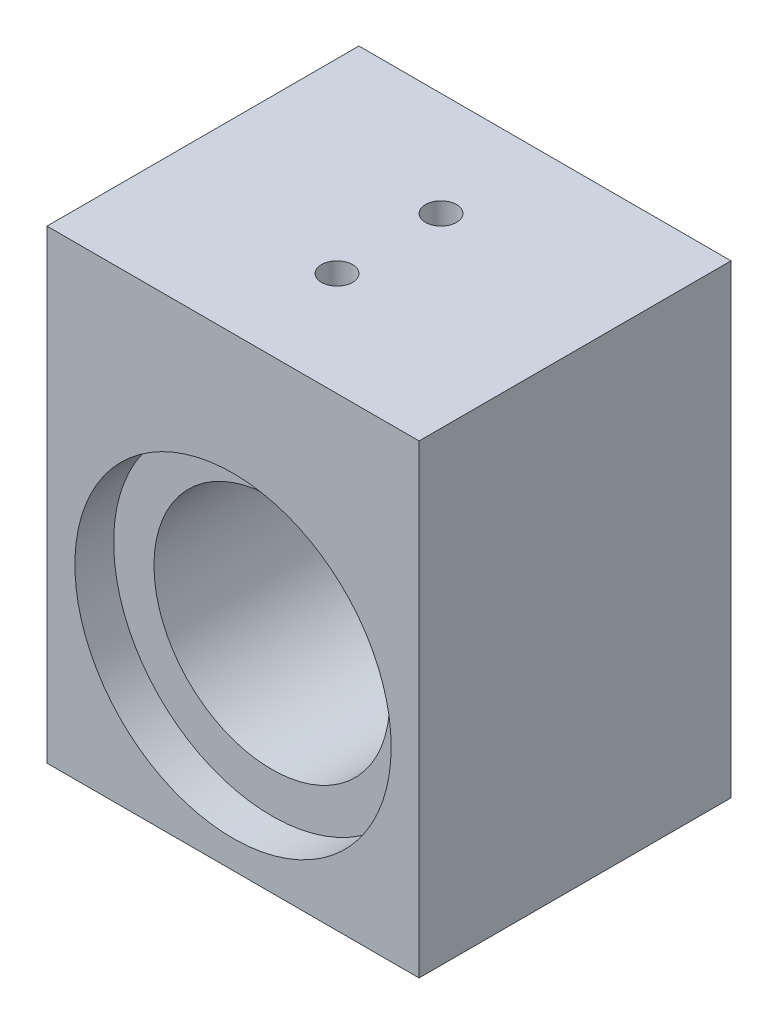
SolidWorks part; units mm, degrees
ref_plane "Front Plane" through (0, 0, 0) normal (0, 0, 1) x (1, 0, 0)
ref_plane "Top Plane" through (0, 0, 0) normal (0, 1, 0) x (1, 0, 0)
ref_plane "Right Plane" through (0, 0, 0) normal (1, 0, 0) x (0, 0, -1)
sketch "Sketch1" plane through (0, 0, 0) normal (0, 0, 1) x (1, 0, 0)
  line L0 (0, 7.62) -> (15.24, 7.62) construction
  line L1 (0, 0) -> (15.24, 0)
  line L2 (0, 0) -> (0, 19.05)
  line L3 (0, 19.05) -> (15.24, 19.05)
  line L4 (15.24, 0) -> (15.24, 19.05)
  circle A0 centre (7.62, 7.62) radius 3.302
  dimension "D1" = 6.604
  dimension "D2" = 15.24
  dimension "D3" = 19.05
  dimension "D4" = 7.62
extrude "Boss-Extrude1" add sketch "Sketch1" along normal blind 12.7762
sketch "Sketch2" plane through (0, 0, 12.7762) normal (0, 0, 1) x (1, 0, 0)
  circle A0 centre (7.62, 7.62) radius 3.302 construction
  circle A1 centre (7.62, 7.62) radius 3.302
  circle A2 centre (7.62, 7.62) radius 4.826
  dimension "D1" = 9.652
extrude "Cut-Extrude1" cut sketch "Sketch2" against normal offset from surface (9.6012 mm away) 3.175 up to face at (7.62, 9.525, 0)
sketch "Sketch4" plane through (0, 0, 12.7762) normal (0, 0, 1) x (1, 0, 0)
  circle A0 centre (7.62, 7.62) radius 4.826 construction
  circle A1 centre (7.62, 7.62) radius 4.826 construction
  circle A2 centre (7.62, 7.62) radius 6.477
  dimension "D1" = 12.954
extrude "Cut-Extrude4" cut sketch "Sketch4" against normal blind 1.5875
sketch "Sketch5" plane through (0, 19.05, 0) normal (0, 1, 0) x (1, 0, 0)
  line L0 (7.62, -4.2587) -> (7.62, -8.5175) construction
  line L1 (7.62, -12.7762) -> (7.62, -8.5175) construction
  line L2 (15.24, -12.7762) -> (0, -12.7762) construction
  line L3 (7.62, -4.2587) -> (7.62, 0) construction
  line L4 (15.24, 0) -> (0, 0) construction
  circle A0 centre (7.62, -8.5175) radius 0.635
  circle A1 centre (7.62, -4.2587) radius 0.635
  dimension "D1" = 1.27
extrude "Cut-Extrude5" cut sketch "Sketch5" against normal blind 2.54
equation "\"D1@Boss-Extrude1\"=0.125+0.378"
